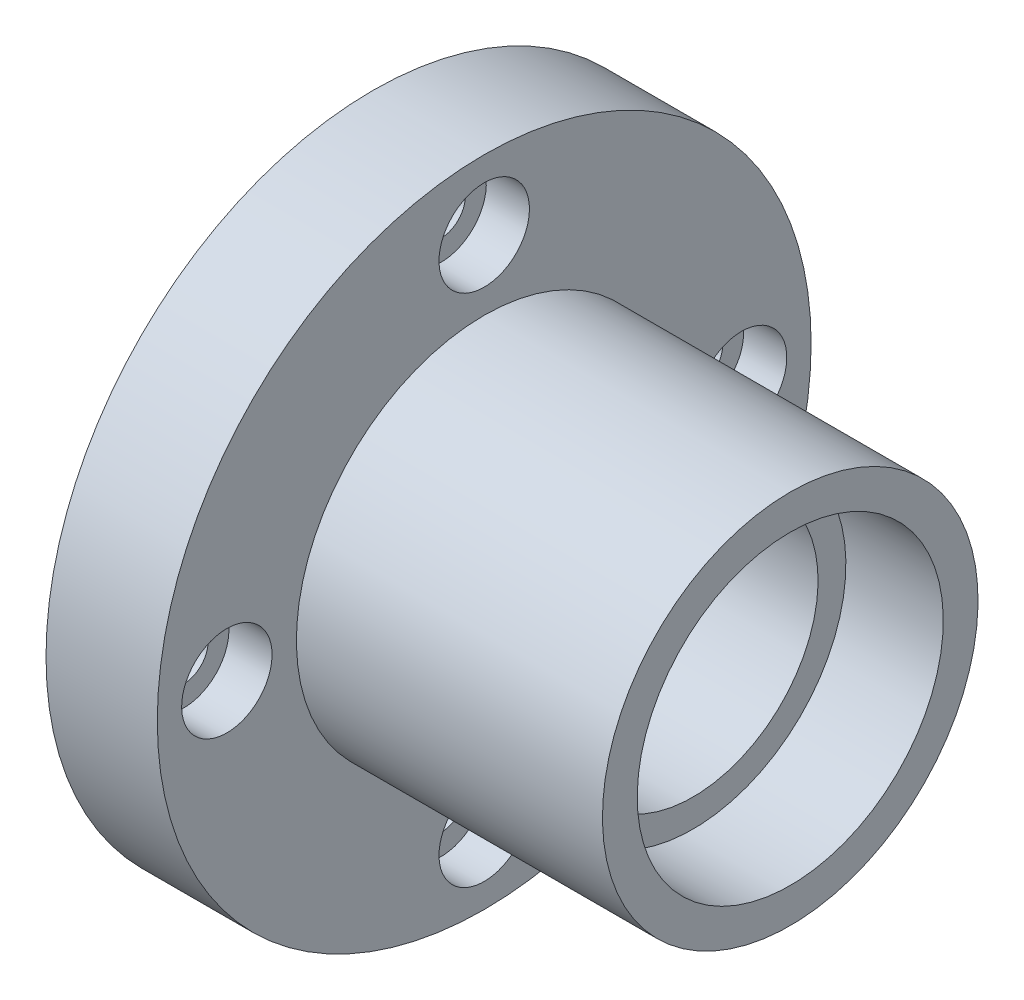
SolidWorks part; units mm, degrees
ref_plane "前视基准面" through (0, 0, 0) normal (0, 0, 1) x (1, 0, 0)
ref_plane "上视基准面" through (0, 0, 0) normal (0, 1, 0) x (1, 0, 0)
ref_plane "右视基准面" through (0, 0, 0) normal (1, 0, 0) x (0, 0, -1)
sketch "草图1" plane through (0, 0, 0) normal (0, 0, 1) x (1, 0, 0)
  line L0 (0, 0) -> (-100.351, 0) construction
  line L1 (-17.5, 13.5) -> (-17.5, 11)
  line L6 (-17.5, 11) -> (-10.5, 11)
  line L7 (-10.5, 11) -> (-10.5, 9)
  line L8 (-10.5, 9) -> (10.5, 9)
  line L9 (10.5, 9) -> (10.5, 11)
  line L10 (-17.5, 13.5) -> (-12.5, 13.5)
  line L11 (10.5, 11) -> (17.5, 11)
  line L16 (0, 0) -> (0, 9) construction
  line L17 (-12.5, 13.5) -> (-12.5, 23.5)
  line L18 (-12.5, 23.5) -> (-4.5, 23.5)
  line L19 (-4.5, 23.5) -> (-4.5, 13.5)
  line L20 (-4.5, 13.5) -> (17.5, 13.5)
  line L21 (17.5, 13.5) -> (17.5, 11)
  dimension "D1" = 47
  dimension "D2" = 8
  dimension "D3" = 5
  dimension "D4" = 7
  dimension "D5" = 18
  dimension "D6" = 22
  dimension "D10" = 35
  dimension "D11" = 27
revolve "旋转1" add sketch "草图1" angle 360 about L0
sketch "草图2" plane through (-4.5, 0, 0) normal (1, 0, 0) x (0, 0, -1)
  circle A0 centre (0, 0) radius 18.5 construction
  circle A1 centre (0, 18.5) radius 3.25
  circle A2 centre (0, -18.5) radius 3.25
  circle A3 centre (18.5, 0) radius 3.25
  circle A4 centre (-18.5, 0) radius 3.25
  dimension "D1" = 37
  dimension "D2" = 6.5
extrude "切除-拉伸1" cut sketch "草图2" against normal blind 3.1
sketch "草图3" plane through (-4.5, 0, 0) normal (1, 0, 0) x (0, 0, -1)
  circle A0 centre (0, 0) radius 18.5 construction
  circle A1 centre (0, 18.5) radius 1.75
  circle A2 centre (18.5, 0) radius 1.75
  circle A3 centre (0, -18.5) radius 1.75
  circle A4 centre (-18.5, 0) radius 1.75
  dimension "D1" = 37
  dimension "D2" = 3.5
extrude "切除-拉伸2" cut sketch "草图3" against normal through all
sketch "草图4" plane through (-4.5, 0, 0) normal (1, 0, 0) x (0, 0, -1)
  line L0 (0, 0) -> (0, 19.5311) construction
  line L1 (23.4109, -2.045) -> (2.045, -23.4109)
  line L2 (2.045, 23.4109) -> (23.4109, 2.045)
  line L3 (-2.045, 23.4109) -> (-23.4109, 2.045)
  line L4 (-23.4109, -2.045) -> (-2.045, -23.4109)
  line L5 (0, 0) -> (12.7279, 12.7279) construction
  arc A0 (23.4109, 2.045) -> (2.045, 23.4109) centre (0, 0) ccw
  arc A2 (-23.4109, -2.045) -> (-2.045, -23.4109) centre (0, 0) ccw
  arc A3 (2.045, -23.4109) -> (23.4109, -2.045) centre (0, 0) ccw
  arc A4 (-2.045, 23.4109) -> (-23.4109, 2.045) centre (0, 0) ccw
  circle A5 centre (0, 0) radius 23.5 construction
  dimension "D1" = 45
  dimension "D2" = 36
extrude "切除-拉伸3" [suppressed] cut sketch "草图4" against normal through all
sketch "草图5" plane through (-4.5, 0, 0) normal (1, 0, 0) x (0, 0, -1)
  line L0 (-14.5, 18.4932) -> (-14.5, -18.4932)
  line L1 (0, 0) -> (0, 9.9439) construction
  line L2 (14.5, 18.4932) -> (14.5, -18.4932)
  arc A0 (-14.5, 18.4932) -> (-14.5, -18.4932) centre (0, 0) ccw
  arc A2 (14.5, -18.4932) -> (14.5, 18.4932) centre (0, 0) ccw
  circle A3 centre (0, 0) radius 23.5 construction
  dimension "D1" = 29
extrude "切除-拉伸4" [suppressed] cut sketch "草图5" against normal through all
sketch "草图7" plane through (-4.5, 0, 0) normal (1, 0, 0) x (0, 0, -1)
  line L0 (0, 0) -> (11.1316, 0) construction
  circle A0 centre (0, 18.5) radius 3.25
  circle A2 centre (0, -18.5) radius 3.25
  dimension "D2" = 6.5
  dimension "D1" = 37
extrude "切除-拉伸6" [suppressed] cut sketch "草图7" against normal blind 3.1
sketch "草图8" plane through (-4.5, 0, 0) normal (1, 0, 0) x (0, 0, -1)
  line L0 (0, 0) -> (-11.7742, 0) construction
  circle A0 centre (0, 18.5) radius 1.75
  circle A1 centre (0, -18.5) radius 1.75
  dimension "D2" = 3.5
  dimension "D1" = 37
extrude "切除-拉伸7" [suppressed] cut sketch "草图8" against normal through all
sketch "草图9" plane through (-4.5, 0, 0) normal (1, 0, 0) x (0, 0, -1)
  line L0 (0, 0) -> (0, 56.5777) construction
  line L1 (0, 0) -> (-44.1221, 0) construction
  circle A0 centre (-25.5, 18.5) radius 3.25
  circle A1 centre (25.5, 18.5) radius 3.25
  circle A2 centre (25.5, -18.5) radius 3.25
  circle A3 centre (-25.5, -18.5) radius 3.25
  dimension "D3" = 6.5
  dimension "D1" = 37
  dimension "D2" = 51
extrude "切除-拉伸8" [suppressed] cut sketch "草图9" against normal blind 3.1
sketch "草图11" plane through (-4.5, 0, 0) normal (1, 0, 0) x (0, 0, -1)
  line L0 (0, 0) -> (0, 47.4167) construction
  line L1 (0, 0) -> (-40.3031, 0) construction
  circle A0 centre (-25.5, 18.5) radius 1.75
  circle A1 centre (25.5, 18.5) radius 1.75
  circle A2 centre (25.5, -18.5) radius 1.75
  circle A3 centre (-25.5, -18.5) radius 1.75
  dimension "D3" = 3.5
  dimension "D1" = 37
  dimension "D2" = 51
extrude "切除-拉伸9" [suppressed] cut sketch "草图11" against normal through all
